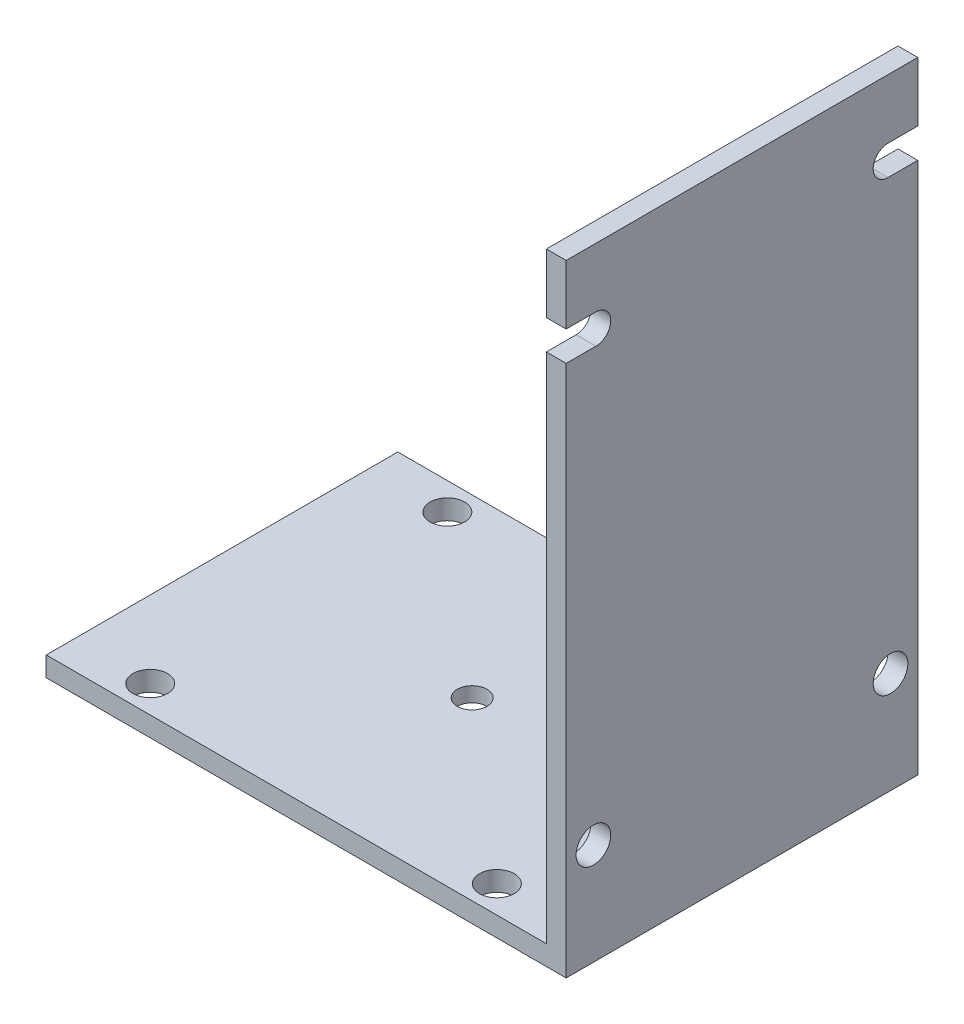
SolidWorks part; units mm, degrees
ref_plane "Alzado" through (0, 0, 0) normal (0, 0, 1) x (1, 0, 0)
ref_plane "Planta" through (0, 0, 0) normal (0, 1, 0) x (1, 0, 0)
ref_plane "Vista lateral" through (0, 0, 0) normal (1, 0, 0) x (0, 0, -1)
sketch "Croquis1" plane through (0, 0, 0) normal (0, 1, 0) x (1, 0, 0)
  line L0 (40.2206, -36) -> (40.2206, -34)
  line L1 (-45.2794, 35) -> (55.7206, 35)
  line L2 (-45.2794, 35) -> (-45.2794, -36)
  line L3 (-45.2794, -36) -> (55.7206, -36)
  line L4 (55.7206, 35) -> (55.7206, -36)
  line L5 (43.7206, -30.5) -> (55.7206, -30.5)
  line L6 (-29.7794, -34) -> (-29.7794, -36)
  line L7 (-33.2794, -30.5) -> (-45.2794, -30.5)
  line L8 (43.7206, 29.5) -> (55.7206, 29.5)
  line L9 (40.2206, 33) -> (40.2206, 35)
  line L10 (-33.2794, 29.5) -> (-45.2794, 29.5)
  line L11 (-29.7794, 33) -> (-29.7794, 35)
  circle A0 centre (40.2206, -30.5) radius 3.5
  circle A1 centre (-29.7794, -30.5) radius 3.5
  circle A2 centre (40.2206, 29.5) radius 3.5
  circle A3 centre (-29.7794, 29.5) radius 3.5
  point P0 (0, 0)
  dimension "D5" = 7
  dimension "D8" = 7
  dimension "D9" = 7
  dimension "D12" = 7
  dimension "D1" = 71
  dimension "D2" = 101
  dimension "D3" = 2
  dimension "D4" = 12
  dimension "D6" = 2
  dimension "D7" = 12
  dimension "D10" = 12
  dimension "D11" = 2
  dimension "D13" = 12
  dimension "D14" = 2
extrude "Saliente-Extruir1" add sketch "Croquis1" along normal blind 4 contours A3 L10 L2 L7 A1 L6 L3 L0 A0 L5 L4 L8 A2 L9 L1 L11 | A1 L7 L2 L3 L6 | A0 L0 L3 L4 L5 | A2 L8 L4 L1 L9 | A3 L11 L1 L2 L10
sketch "Croquis2" plane through (0, 0, 0) normal (0, 1, 0) x (1, 0, 0)
  line L1 (55.7206, 35) -> (59.7206, 35)
  line L2 (55.7206, 35) -> (55.7206, -36)
  line L3 (55.7206, -36) -> (59.7206, -36)
  line L4 (59.7206, 35) -> (59.7206, -36)
  dimension "D1" = 71
  dimension "D2" = 4
extrude "Saliente-Extruir2" add sketch "Croquis2" along normal blind 125.5
sketch "Croquis3" plane through (0, 0, 0) normal (1, 0, 0) x (0, 0, -1)
  line L0 (-30.5, 17) -> (-30.5, 4)
  line L1 (29, 107.5) -> (35, 107.5)
  line L2 (-34, 20.5) -> (-36, 20.5)
  line L3 (-36, 125.5) -> (-36, 4) construction
  line L4 (35, 4) -> (-36, 4) construction
  line L5 (29.5, 17) -> (29.5, 4)
  line L6 (35, 4) -> (-36, 4) construction
  line L7 (33, 20.5) -> (35, 20.5)
  line L8 (35, 125.5) -> (35, 4) construction
  line L9 (-27, 110.5) -> (-36, 110.5)
  line L10 (-30, 125.5) -> (-30, 113.5)
  line L11 (35, 125.5) -> (-36, 125.5) construction
  line L12 (-30, 113.5) -> (-36, 113.5)
  line L13 (-36, 113.5) -> (-36, 110.5)
  line L14 (-30, 107.5) -> (-36, 107.5)
  line L15 (-36, 107.5) -> (-36, 110.5)
  line L16 (26, 110.5) -> (35, 110.5)
  line L17 (29, 113.5) -> (29, 125.5)
  line L18 (29, 113.5) -> (35, 113.5)
  line L19 (35, 113.5) -> (35, 110.5)
  line L21 (35, 107.5) -> (35, 110.5)
  circle A0 centre (-30.5, 20.5) radius 3.5
  circle A1 centre (29.5, 20.5) radius 3.5
  arc A2 (-30, 107.5) -> (-30, 113.5) centre (-30, 110.5) ccw
  arc A3 (29, 113.5) -> (29, 107.5) centre (29, 110.5) ccw
  dimension "D2" = 7
  dimension "D5" = 7
  dimension "D7" = 6
  dimension "D10" = 6
  dimension "D1" = 13
  dimension "D3" = 2
  dimension "D4" = 13
  dimension "D6" = 2
  dimension "D8" = 9
  dimension "D9" = 12
  dimension "D11" = 9
  dimension "D12" = 12
extrude "Cortar-Extruir2" cut sketch "Croquis3" along normal up to surface (59.7206 mm away) from surface at 55.7206
sketch "Croquis4" plane through (0, 4, 0) normal (0, 1, 0) x (1, 0, 0)
  line L0 (-45.2794, -0.5) -> (5.2206, -0.5)
  line L3 (-45.2794, 35) -> (-45.2794, -36) construction
  circle A0 centre (5.2206, -0.5) radius 3
  dimension "D2" = 6
  dimension "D1" = 50.5
extrude "Cortar-Extruir3" cut sketch "Croquis4" against normal up to surface (4 mm away) contours A0
sketch "Croquis5" plane through (0, 0, 0) normal (0, -1, 0) x (1, 0, 0)
  circle A0 centre (5.2206, 0.5) radius 12.25
  dimension "D1" = 24.5
extrude "Cortar-Extruir4" cut sketch "Croquis5" against normal blind 1
